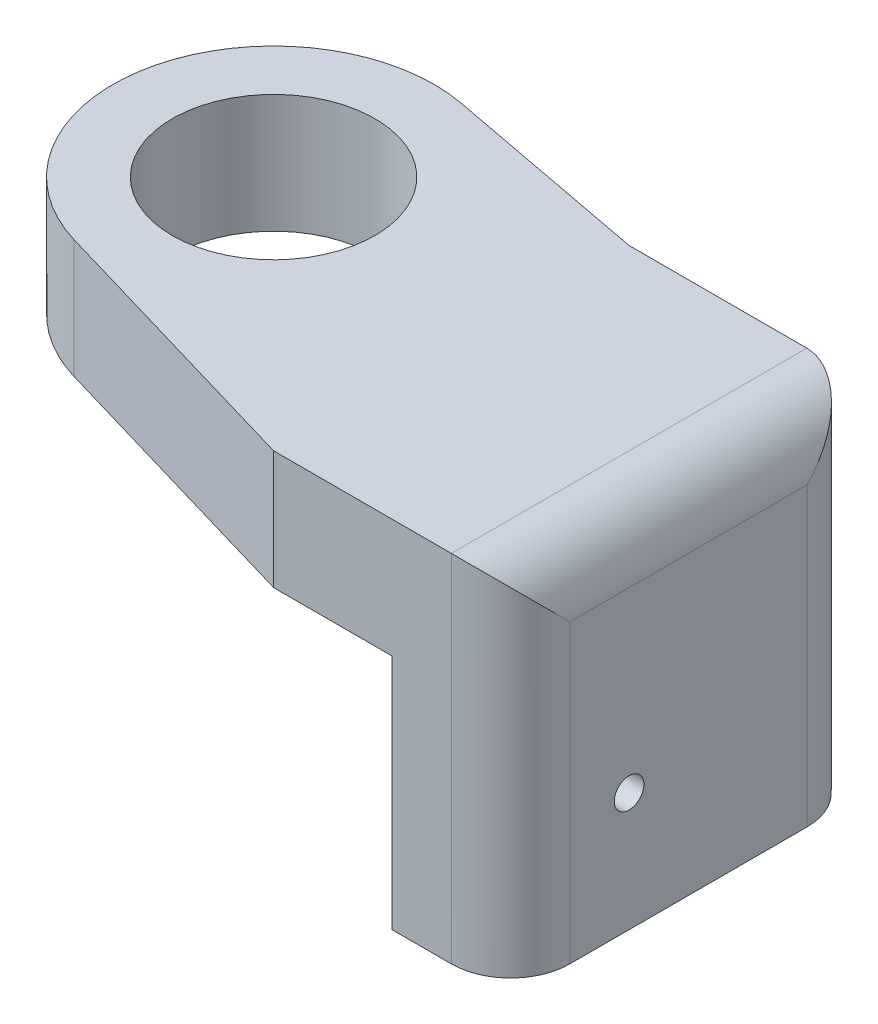
SolidWorks part; units mm, degrees
material "PVC 0.007 Plasticized"
ref_plane "Front Plane" through (0, 0, 0) normal (0, 0, 1) x (1, 0, 0)
ref_plane "Top Plane" through (0, 0, 0) normal (0, 1, 0) x (1, 0, 0)
ref_plane "Right Plane" through (0, 0, 0) normal (1, 0, 0) x (0, 0, -1)
sketch "Sketch1" plane through (0, 0, 0) normal (0, 1, 0) x (1, 0, 0)
  line L1 (0, 0) -> (20, 0)
  line L2 (0, 0) -> (0, -30)
  line L3 (0, -30) -> (20, -30)
  line L4 (20, 0) -> (20, -30)
  dimension "D1" = 30
  dimension "D2" = 20
extrude "Boss-Extrude1" add sketch "Sketch1" along normal blind 10
sketch "Sketch2" plane through (0, 10, 0) normal (0, 1, 0) x (1, 0, 0)
  line L4 (0, 0) -> (0, -10)
  line L5 (0, -10) -> (10, -10)
  line L6 (10, -10) -> (10, -30)
  line L7 (0, -30) -> (20, -30) construction
  line L8 (10, -30) -> (20, -30)
  line L9 (20, -30) -> (20, 0) construction
  line L10 (20, -30) -> (20, 0)
  line L11 (20, 0) -> (0, 0)
  dimension "D1" = 10
  dimension "D2" = 10
extrude "Boss-Extrude2" add sketch "Sketch2" along normal blind 10
sketch "Sketch4" plane through (0, 10, 0) normal (0, 1, 0) x (1, 0, 0)
  line L0 (0, 0) -> (-17.5137, 3.3199)
  line L1 (0, -30) -> (-23.8464, -22.9926)
  line L2 (0, 0) -> (0, -30)
  line L3 (0, 0) -> (0, -30) construction
  line L4 (0, -10) -> (-36.9218, -10) construction
  circle A0 centre (-20, -10) radius 8.55
  arc A1 (-17.5137, 3.3199) -> (-23.8464, -22.9926) centre (-20, -10) ccw
  circle A2 centre (-20, -10) radius 13.55 construction
  dimension "D1" = 17.1
  dimension "D3" = 20
  dimension "D2" = 5
extrude "Boss-Extrude3" add sketch "Sketch4" against normal up to surface (10 mm away) up to face at (10, 0, 15)
ref_plane "Plane1" through (0, 5, 0) normal (0, -1, 0) x (-1, 0, 0)
mirror "Mirror1" about plane through (0, 5, 0) normal (0, -1, 0) of "Boss-Extrude2"
sketch "Sketch5" plane through (0, 20, 0) normal (0, 1, 0) x (1, 0, 0)
  line L6 (20, 0) -> (0, 0)
  line L7 (0, 0) -> (0, -10)
  line L8 (0, -10) -> (10, -10)
  line L9 (10, -10) -> (10, -30)
  line L10 (10, -30) -> (20, -30)
  line L11 (20, -30) -> (20, 0)
  line L12 (20, 0) -> (0, 0)
  line L13 (0, 0) -> (0, -10)
  line L14 (0, -10) -> (10, -10)
  line L15 (10, -10) -> (10, -30)
  line L16 (10, -30) -> (20, -30)
  line L17 (20, -30) -> (20, 0)
  dimension "D1" = 0
extrude "Cut-Extrude1" cut sketch "Sketch5" against normal up to surface (10 mm away) up to face at (-4.8363, 10, 13.8094)
sketch "Sketch6" plane through (0, -10, 0) normal (0, -1, 0) x (1, 0, 0)
  line L6 (0, 0) -> (20, 0)
  line L7 (20, 0) -> (20, 30)
  line L8 (20, 30) -> (10, 30)
  line L9 (10, 30) -> (10, 10)
  line L10 (10, 10) -> (0, 10)
  line L11 (0, 10) -> (0, 0)
  line L12 (0, 0) -> (20, 0)
  line L13 (20, 0) -> (20, 30)
  line L14 (20, 30) -> (10, 30)
  line L15 (10, 30) -> (10, 10)
  line L16 (10, 10) -> (0, 10)
  line L17 (0, 10) -> (0, 0)
  dimension "D1" = 0
extrude "Boss-Extrude4" add sketch "Sketch6" along normal blind 10
sketch "Sketch7" plane through (10, 0, 0) normal (-1, 0, 0) x (0, 0, 1)
  line L0 (30, -20) -> (30, 0) construction
  line L1 (30, -20) -> (10, -20) construction
  circle A0 centre (20, -10) radius 1.25
  point P4 (30, -10)
  point P7 (20, -20)
  dimension "D1" = 2.5
extrude "Cut-Extrude2" cut sketch "Sketch7" against normal up to surface (10 mm away) up to face at (20, -5, 15)
fillet "Fillet1" radius 5 3 edges at (20, -5, 30) (20, 10, 15) (20, -5, 0)
